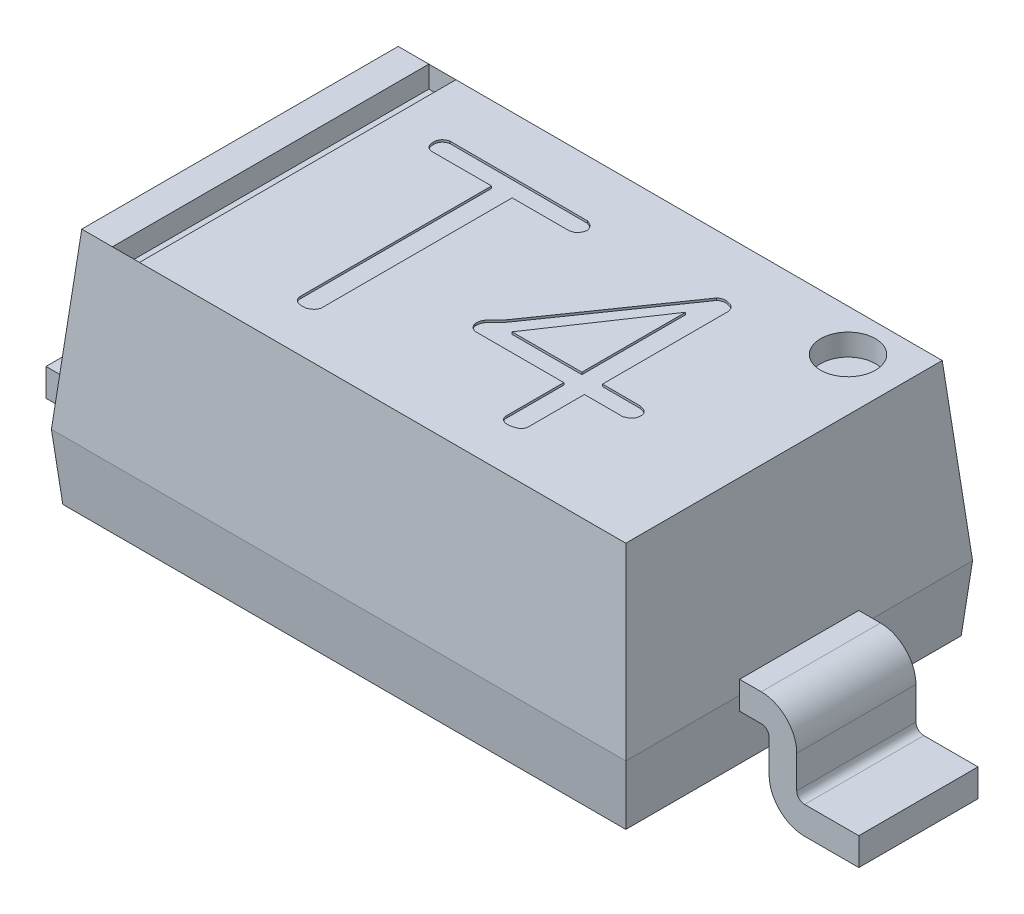
SolidWorks part; units mm, degrees
ref_plane "Front Plane" through (0, 0, 0) normal (0, 0, 1) x (1, 0, 0)
ref_plane "Top Plane" through (0, 0, 0) normal (0, 1, 0) x (1, 0, 0)
ref_plane "Right Plane" through (0, 0, 0) normal (1, 0, 0) x (0, 0, -1)
sketch "Sketch1" plane through (0, 0, 0) normal (0, 1, 0) x (1, 0, 0)
  line L1 (-1.325, 0.8) -> (1.325, 0.8)
  line L2 (-1.325, 0.8) -> (-1.325, -0.8)
  line L3 (-1.325, -0.8) -> (1.325, -0.8)
  line L4 (1.325, 0.8) -> (1.325, -0.8)
  line L5 (-1.325, 0.8) -> (1.325, -0.8) construction
  line L6 (-1.325, -0.8) -> (1.325, 0.8) construction
  point P0 (0, 0)
  dimension "D1" = 1.6
  dimension "D2" = 2.65
extrude "Boss-Extrude1" add sketch "Sketch1" along normal blind 0.8 draft 5 and the other way blind 0.3 draft 5
sketch "Sketch3" plane through (0, 0, 0) normal (0, 0, 1) x (1, 0, 0)
  line L0 (-1.325, 0) -> (-1.425, 0)
  line L1 (-1.525, -0.1) -> (-1.525, -0.25)
  line L2 (-1.625, -0.35) -> (-1.875, -0.35)
  line L3 (0, 0) -> (0, -0.8139) construction
  line L4 (-1.325, 0) -> (1.325, 0) construction
  line L5 (1.625, -0.35) -> (1.875, -0.35)
  line L6 (1.525, -0.1) -> (1.525, -0.25)
  line L7 (1.325, 0) -> (1.425, 0)
  line L8 (-1.2988, -0.3) -> (1.2988, -0.3) construction
  arc A0 (1.525, -0.25) -> (1.625, -0.35) centre (1.625, -0.25) ccw
  arc A1 (1.525, -0.1) -> (1.425, 0) centre (1.425, -0.1) ccw
  arc A2 (-1.525, -0.25) -> (-1.625, -0.35) centre (-1.625, -0.25) cw
  arc A3 (-1.425, 0) -> (-1.525, -0.1) centre (-1.425, -0.1) ccw
  point P24 (1.525, -0.35)
  point P27 (1.525, 0)
  point P30 (-1.525, -0.35)
  point P33 (-1.525, 0)
  dimension "D5" = 0.1
  dimension "D1" = 3.75
  dimension "D2" = 0.35
  dimension "D3" = 0.05
  dimension "D4" = 3.05
extrude "Extrude-Thin1" add sketch "Sketch3" along normal mid plane 0.55 separate body thin thin type mid plane wall 0.1275
sketch "Sketch4" plane through (0, 0.8, 0) normal (0, 1, 0) x (1, 0, 0)
  line L3 (-0.7797, -0.5051) -> (1.1786, -0.5051) construction
  text T0 "T4" font "SWSimp" height 1
extrude "Cut-Extrude2" cut sketch "Sketch4" against normal blind 0.01
sketch "Sketch5" plane through (0, 0.8, 0) normal (0, 1, 0) x (1, 0, 0)
  line L0 (-1.0511, 0.73) -> (-1.0511, -0.73)
  line L1 (1.255, 0.73) -> (-1.255, 0.73) construction
  line L2 (-1.255, -0.73) -> (1.255, -0.73) construction
  circle A0 centre (1.0135, 0.5369) radius 0.0639
extrude "Cut-Extrude-Thin1" cut sketch "Sketch5" against normal blind 0.1 thin contours A0 | L0 thin type mid plane wall 0.125
sketch "Sketch6" plane through (0, 0.7, 0) normal (0, 1, 0) x (1, 0, 0)
  circle A1 centre (1.0135, 0.5369) radius 0.1264
  circle A2 centre (1.0135, 0.5369) radius 0.1264
  dimension "D1" = 0
extrude "Cut-Extrude3" cut sketch "Sketch6" along normal blind 0.1
